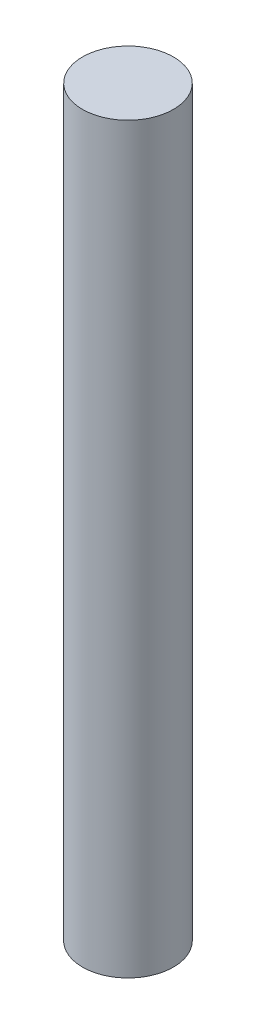
SolidWorks part; units mm, degrees
ref_plane "前视基准面" through (0, 0, 0) normal (0, 0, 1) x (1, 0, 0)
ref_plane "上视基准面" through (0, 0, 0) normal (0, 1, 0) x (1, 0, 0)
ref_plane "右视基准面" through (0, 0, 0) normal (1, 0, 0) x (0, 0, -1)
other "Configuration Table"
sketch "草图1" plane through (0, 0, 0) normal (0, 1, 0) x (1, 0, 0)
  circle A0 centre (0, 0) radius 0.6
  dimension "D1" = 1.2
extrude "凸台-拉伸1" add sketch "草图1" along normal blind 9.8
